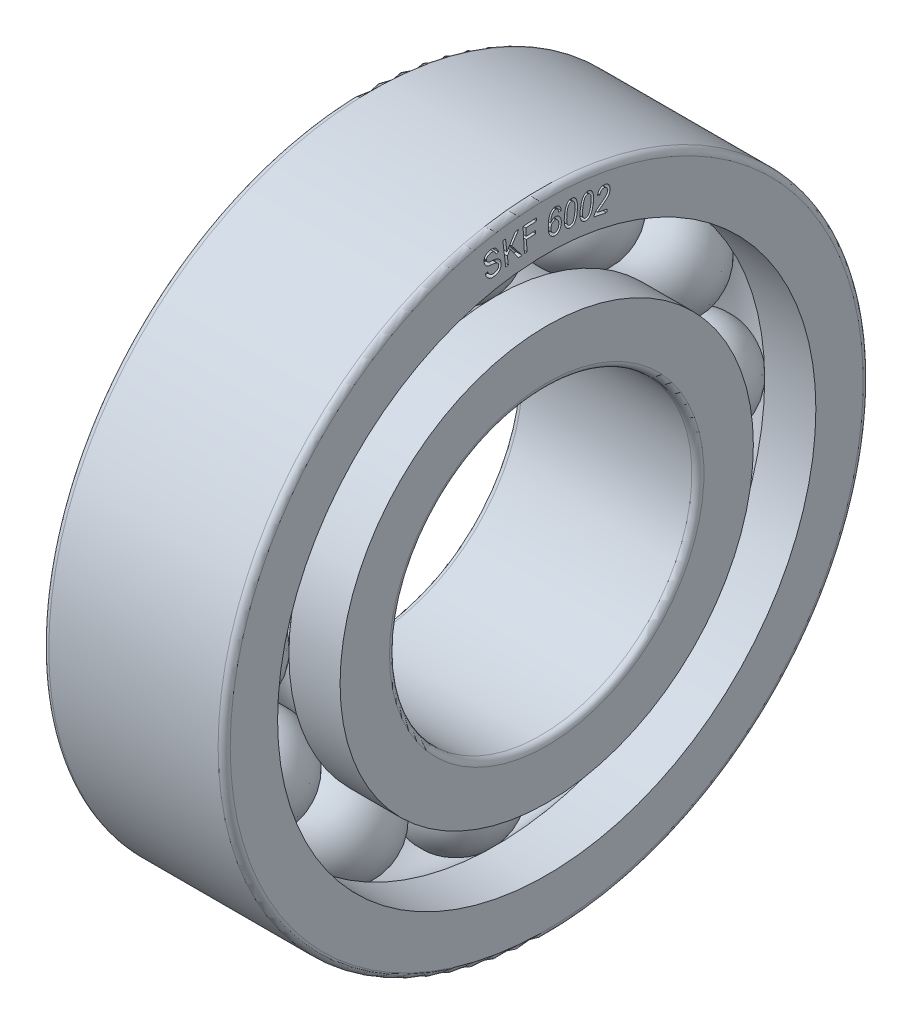
SolidWorks part; units mm, degrees
ref_plane "Alzado" through (0, 0, 0) normal (0, 0, 1) x (1, 0, 0)
ref_plane "Planta" through (0, 0, 0) normal (0, 1, 0) x (1, 0, 0)
ref_plane "Vista lateral" through (0, 0, 0) normal (1, 0, 0) x (0, 0, -1)
sketch "Sketch1" plane through (0, 0, 0) normal (0, 0, 1) x (1, 0, 0)
  line L0 (0, 0) -> (29.9021, 0) construction
  line L1 (0, 13.35) -> (2.5385, 13.35)
  line L2 (0, 16) -> (9, 16)
  line L3 (0, 16) -> (0, 13.35)
  line L4 (0, 7.5) -> (9, 7.5)
  line L5 (9, 16) -> (9, 13.35)
  line L6 (0, 10.25) -> (2.5385, 10.25)
  line L7 (0, 10.25) -> (0, 7.5)
  line L8 (9, 10.25) -> (9, 7.5)
  line L9 (0, 13.35) -> (0, 10.25) construction
  line L10 (0, 11.8) -> (9, 11.8) construction
  line L11 (6.4615, 10.25) -> (9, 10.25)
  line L12 (6.4615, 13.35) -> (9, 13.35)
  arc A0 (2.5385, 10.25) -> (6.4615, 10.25) centre (4.5, 11.8) ccw
  arc A1 (6.4615, 13.35) -> (2.5385, 13.35) centre (4.5, 11.8) ccw
  dimension "D6" = 5
  dimension "D1" = 9
  dimension "D2" = 7.5
  dimension "D3" = 16
  dimension "D4" = 13.35
  dimension "D5" = 10.25
revolve "Revolve1" add sketch "Sketch1" angle 360 about L0
fillet "Fillet1" radius 0.3 2 edges at (0, 0, 16) (9, 0, 16)
fillet "Fillet2" radius 0.3 2 edges at (0, 0, 7.5) (9, 0, 7.5)
sketch "Sketch2" plane through (0, 0, 0) normal (0, 0, 1) x (1, 0, 0)
  line L0 (4.5, 14.3) -> (4.5, 9.3)
  arc A0 (4.5, 14.3) -> (4.5, 9.3) centre (4.5, 11.8) ccw
  arc A1 (6.4615, 13.35) -> (2.5385, 13.35) centre (4.5, 11.8) ccw construction
revolve "Revolve2" add sketch "Sketch2" angle 360 about L0
pattern_circular "CirPattern2" count 12 over 360 about axis through (0, 0, 0) along (1, 0, 0) of bodies 103
sketch "Sketch4" plane through (9, 0, 0) normal (1, 0, 0) x (0, 0, -1)
  arc A0 (-4.7515, 13.1159) -> (4.7515, 13.1159) centre (0, 0) cw construction
  circle A1 centre (0, 0) radius 13.35 construction
  text T0 "SKF 6002\r\n" font "Arial Narrow" height 1.2
  dimension "D1" = 0.6
extrude "Cut-Extrude1" cut sketch "Sketch4" against normal blind 0.3
